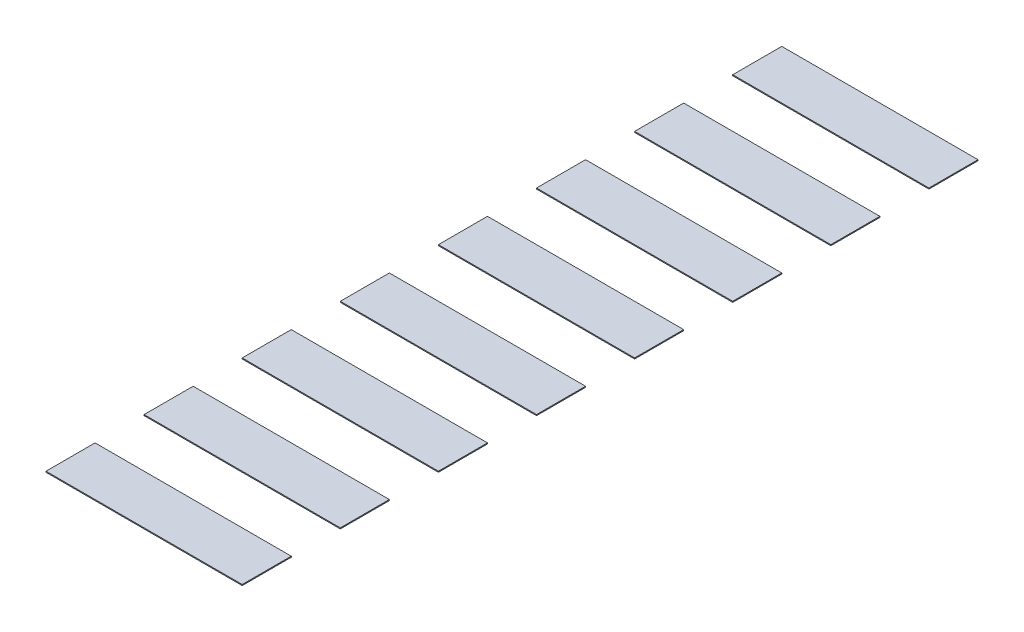
SolidWorks part; units mm, degrees
ref_plane "前视基准面" through (0, 0, 0) normal (0, 0, 1) x (1, 0, 0)
ref_plane "上视基准面" through (0, 0, 0) normal (0, 1, 0) x (1, 0, 0)
ref_plane "右视基准面" through (0, 0, 0) normal (1, 0, 0) x (0, 0, -1)
sketch "草图1" plane through (0, 0, 0) normal (0, 1, 0) x (1, 0, 0)
  line L0 (0, -50) -> (100, -50)
  line L1 (0, 0) -> (100, 0)
  line L2 (0, 0) -> (0, -25)
  line L3 (0, -25) -> (100, -25)
  line L4 (100, 0) -> (100, -25)
  line L5 (0, -50) -> (0, -75)
  line L6 (0, -75) -> (100, -75)
  line L7 (100, -50) -> (100, -75)
  line L8 (0, -175) -> (100, -175)
  line L9 (100, -150) -> (100, -175)
  line L10 (0, -150) -> (0, -175)
  line L11 (0, -100) -> (0, -125)
  line L12 (100, -100) -> (100, -125)
  line L13 (0, -100) -> (100, -100)
  line L14 (0, -150) -> (100, -150)
  line L15 (0, -125) -> (100, -125)
  line L16 (0, -350) -> (100, -350)
  line L17 (0, -200) -> (100, -200)
  line L18 (0, -250) -> (0, -275)
  line L19 (0, -275) -> (100, -275)
  line L20 (100, -300) -> (100, -325)
  line L21 (0, -300) -> (0, -325)
  line L22 (100, -350) -> (100, -375)
  line L23 (0, -225) -> (100, -225)
  line L24 (0, -250) -> (100, -250)
  line L25 (0, -375) -> (100, -375)
  line L26 (0, -200) -> (0, -225)
  line L27 (0, -350) -> (0, -375)
  line L28 (100, -250) -> (100, -275)
  line L29 (0, -325) -> (100, -325)
  line L30 (100, -200) -> (100, -225)
  line L31 (0, -300) -> (100, -300)
  dimension "D1" = 100
  dimension "D2" = 25
  dimension "D3" = 100
  dimension "D4" = 25
  dimension "D5" = 100
  dimension "D6" = 25
  dimension "D7" = 100
  dimension "D8" = 25
  dimension "D9" = 100
  dimension "D10" = 25
  dimension "D11" = 100
  dimension "D12" = 25
  dimension "D13" = 100
  dimension "D14" = 25
  dimension "D15" = 100
  dimension "D16" = 25
  dimension "D17" = 25
  dimension "D18" = 25
  dimension "D19" = 25
  dimension "D20" = 25
  dimension "D21" = 25
  dimension "D22" = 25
  dimension "D23" = 25
extrude "凸台-拉伸1" add sketch "草图1" along normal blind 0.5
